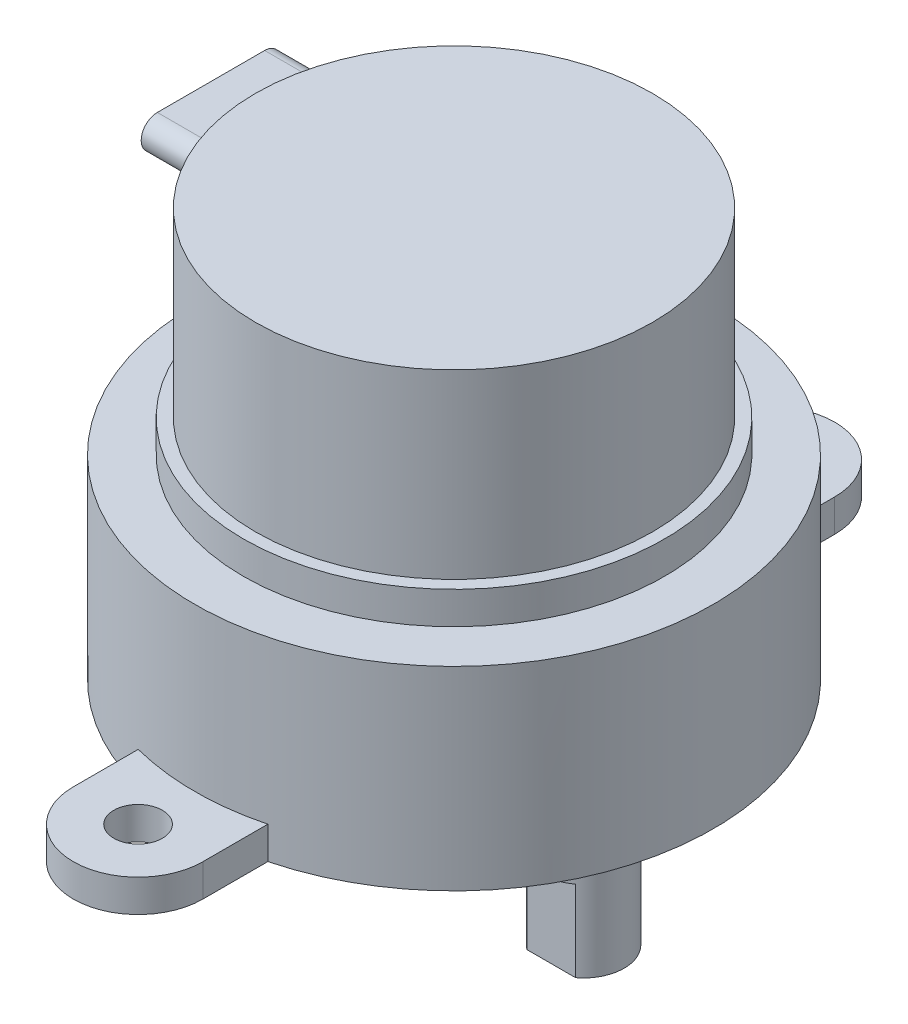
SolidWorks part; units mm, degrees
ref_plane "前视基准面" through (0, 0, 0) normal (0, 0, 1) x (1, 0, 0)
ref_plane "上视基准面" through (0, 0, 0) normal (0, 1, 0) x (1, 0, 0)
ref_plane "右视基准面" through (0, 0, 0) normal (1, 0, 0) x (0, 0, -1)
sketch "草图3" plane through (0, 0, 0) normal (0, 0, 1) x (1, 0, 0)
  line L0 (0, 0) -> (-19.5051, 0) construction
  line L1 (0, -9.2931) -> (0, 15.6319) construction
  line L2 (-16, 0) -> (-16, 12)
  line L3 (-16, 12) -> (-13, 12)
  line L4 (-13, 12) -> (-13, 14)
  line L5 (-13, 14) -> (-12.25, 14)
  line L6 (-12.25, 14) -> (-12.25, 25.2)
  line L7 (-12.25, 25.2) -> (0, 25.2)
  line L8 (0, 0) -> (0, 25.2)
  line L14 (0, 0) -> (-16, 0)
  dimension "D1" = 32
  dimension "D2" = 26
  dimension "D3" = 24.5
  dimension "D4" = 2
  dimension "D5" = 25.2
  dimension "D6" = 12
revolve "旋转1" add sketch "草图3" angle 360 about L8
sketch "草图6" plane through (0, 0, 0) normal (0, 0, 1) x (1, 0, 0)
  line L0 (3.5, 0) -> (3.5, -1.25)
  line L1 (-16, 0) -> (16, 0) construction
  line L2 (3.5, -1.25) -> (4, -1.25)
  line L3 (4, -1.25) -> (4, -2.7)
  line L4 (4, -2.7) -> (5.5, -2.7)
  line L5 (5.5, -2.7) -> (5.5, -10.2)
  line L6 (8, -10.2) -> (5.5, -10.2)
  line L7 (8, -10.2) -> (8, -5.2)
  line L9 (8, 0) -> (8, -13.4458) construction
  line L10 (3.5, 0) -> (8, 0)
  line L11 (8, 0) -> (8, -5.2)
  dimension "D1" = 2.7
  dimension "D2" = 1.25
  dimension "D3" = 5
  dimension "D4" = 8
  dimension "D5" = 10.2
  dimension "D6" = 8
  dimension "D7" = 9
revolve "旋转4" add sketch "草图6" angle 360 about L9
hole_wizard "M3 螺纹孔1" positions "草图7" profile "草图8" tap size "M3" standard "GB"
sketch "草图7" plane through (0, -10.2, 0) normal (0, -1, 0) x (-1, 0, 0)
  point P0 (-8, 0)
cosmetic thread "孔螺蚊线1" parameters "D1"=6, "D2"=3
sketch "草图8" plane through (8, -10.2, 0) normal (1, 0, 0) x (0, 0, -1)
  line L0 (0, 0) -> (0, 8.2511)
  line L1 (0, 8.2511) -> (1.25, 7.5)
  line L2 (1.25, 7.5) -> (1.25, 0)
  line L5 (1.25, 0) -> (0, 0)
  line L10 (0, 8.2511) -> (-1.25, 7.5) construction
  line L11 (0, -6.35) -> (0, 107.95) construction
  dimension "螺纹孔钻头直径" = 2.5
  dimension "螺纹孔钻头深度" = 7.5
  dimension "导头角度" = 118
sketch "草图9" plane through (0, -10.2, 0) normal (0, -1, 0) x (1, 0, 0)
  line L0 (8, 0) -> (16, 0) construction
  line L6 (5.3273, 3.6203) -> (11.0255, 3.6203)
  line L7 (5.3273, 3.6203) -> (5.3273, 2)
  line L8 (5.3273, 2) -> (11.0255, 2)
  line L9 (11.0255, 3.6203) -> (11.0255, 2)
  line L10 (3.6255, -2) -> (11.0255, -2)
  line L11 (3.6255, -2) -> (3.6255, -5.4824)
  line L12 (3.6255, -5.4824) -> (11.0255, -5.4824)
  line L13 (11.0255, -2) -> (11.0255, -5.4824)
  circle A0 centre (0, 0) radius 16 construction
  circle A1 centre (8, 0) radius 4.5 construction
  point P6 (2.5735, 6.0336)
  dimension "D1" = 4
extrude "切除-拉伸1" cut sketch "草图9" against normal blind 5
sketch "草图10" plane through (0, 0, 0) normal (0, -1, 0) x (1, 0, 0)
  line L0 (0, -14.5462) -> (0, 14.7217) construction
  line L1 (0, -19.5) -> (0, 19.5) construction
  line L2 (-4, -19.5) -> (-4, 19.5)
  line L3 (4, -19.5) -> (4, 19.5)
  arc A0 (-4, -19.5) -> (4, -19.5) centre (0, -19.5) ccw
  arc A1 (4, 19.5) -> (-4, 19.5) centre (0, 19.5) ccw
  circle A2 centre (0, 19.5) radius 1.5
  circle A3 centre (0, -19.5) radius 1.5
  point P5 (0, 0)
  dimension "D3" = 3
  dimension "D1" = 8
  dimension "D2" = 39
extrude "凸台-拉伸5" add sketch "草图10" against normal blind 2
sketch "草图11" plane through (0, 0, 0) normal (1, 0, 0) x (0, 0, -1)
  line L0 (0, 25.2) -> (0, 23.4612) construction
  line L1 (12.25, 25.2) -> (-12.25, 25.2) construction
  line L2 (-3.3118, 23.4612) -> (3.3118, 23.4612) construction
  line L3 (-3.3118, 24.4573) -> (3.3118, 24.4573)
  line L4 (-3.3118, 22.4652) -> (3.3118, 22.4652)
  arc A0 (-3.3118, 24.4573) -> (-3.3118, 22.4652) centre (-3.3118, 23.4612) ccw
  arc A1 (3.3118, 22.4652) -> (3.3118, 24.4573) centre (3.3118, 23.4612) ccw
  point P6 (0, 23.4612)
extrude "凸台-拉伸6" add sketch "草图11" against normal blind 15
